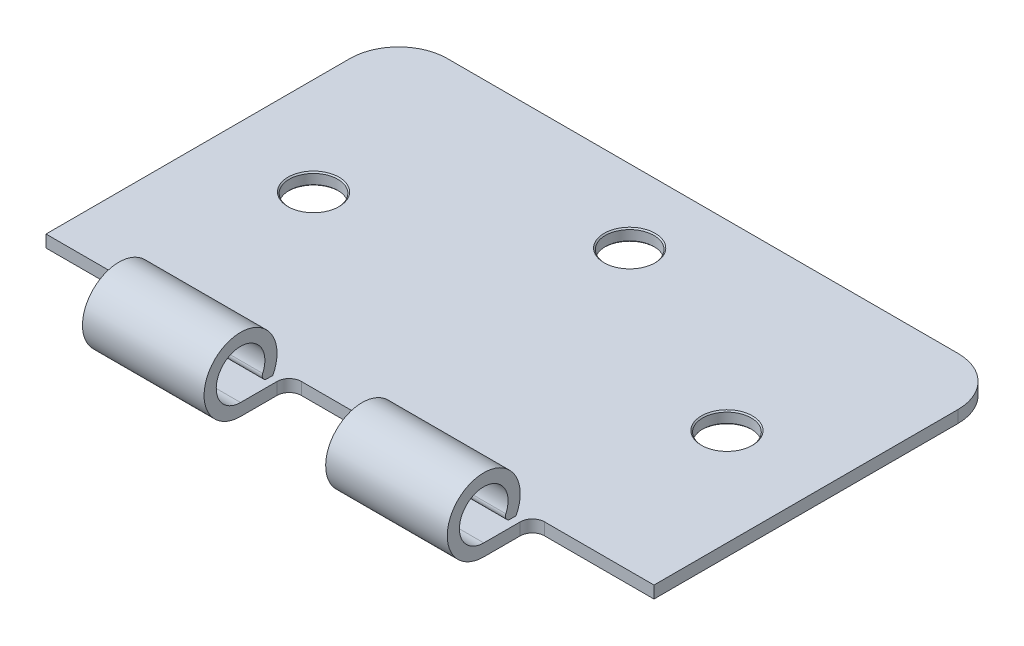
SolidWorks part; units mm, degrees
ref_plane "Front Plane" through (0, 0, 0) normal (0, 0, 1) x (1, 0, 0)
ref_plane "Top Plane" through (0, 0, 0) normal (0, 1, 0) x (1, 0, 0)
ref_plane "Right Plane" through (0, 0, 0) normal (1, 0, 0) x (0, 0, -1)
sketch "Sketch1" plane through (0, 0, 0) normal (0, 1, 0) x (1, 0, 0)
  line L1 (-105, 150) -> (105, 150)
  line L2 (-125, 130) -> (-125, 0)
  line L3 (-125, 0) -> (125, 0)
  line L4 (125, 130) -> (125, 0)
  line L5 (-125, 150) -> (125, 0) construction
  line L6 (-125, 0) -> (125, 150) construction
  arc A0 (105, 150) -> (125, 130) centre (105, 130) cw
  arc A1 (-105, 150) -> (-125, 130) centre (-105, 130) ccw
  circle A2 centre (-85, 75) radius 10
  circle A3 centre (85, 75) radius 10
  circle A4 centre (0, 120) radius 10
  point P0 (0, 75)
  dimension "D3" = 20
  dimension "D8" = 20
  dimension "D1" = 250
  dimension "D2" = 150
  dimension "D4" = 40
  dimension "D5" = 75
  dimension "D6" = 30
  dimension "D7" = 40
extrude "Boss-Extrude1" add sketch "Sketch1" along normal blind 5
sketch "Sketch2" plane through (0, 0, 0) normal (1, 0, 0) x (0, 0, -1)
  line L0 (0, 0) -> (130, 0) construction
  line L1 (0, 5) -> (0, 0) construction
  line L2 (0, 0) -> (-15, 0)
  line L3 (0, 5) -> (-15, 5)
  line L4 (-1.7335, 8) -> (-4.0913, 8)
  line L5 (0, 5) -> (130, 5) construction
  line L6 (0, 0) -> (0, 5)
  arc A0 (-1.7335, 8) -> (-15, 0) centre (-15, 15) ccw
  arc A1 (-5.9094, 10.8333) -> (-15, 5) centre (-15, 15) ccw
  arc A2 (-4.0913, 8) -> (-5.9094, 10.8333) centre (-4.0913, 10) cw
  dimension "D1" = 30
  dimension "D2" = 20
  dimension "D4" = 2
  dimension "D3" = 3
extrude "Boss-Extrude2" add sketch "Sketch2" along normal mid plane 250
sketch "Sketch3" plane through (0, 0, 0) normal (0, 1, 0) x (1, 0, 0)
  line L0 (-125, 0) -> (-125, -30) construction
  line L1 (-75, 5) -> (-125, 5)
  line L2 (-75, 5) -> (-75, -30)
  line L3 (-75, -30) -> (-125, -30)
  line L4 (-125, 5) -> (-125, -30)
  line L5 (-125, -30) -> (125, -30) construction
  line L7 (-25, -30) -> (25, -30)
  line L8 (-25, -30) -> (-25, 5)
  line L9 (-25, 5) -> (25, 5)
  line L10 (25, -30) -> (25, 5)
  line L11 (75, -30) -> (125, -30)
  line L12 (75, -30) -> (75, 5)
  line L13 (75, 5) -> (125, 5)
  line L14 (125, -30) -> (125, 5)
  dimension "D1" = 50
  dimension "D2" = 35
  dimension "D3" = 50
  dimension "D4" = 50
  dimension "D5" = 50
  dimension "D6" = 50
extrude "Cut-Extrude1" cut sketch "Sketch3" along normal mid plane 60
fillet "Fillet1" radius 5 4 edges at (-75, 2.5, -5) (-25, 2.5, -5) (25, 2.5, -5) (75, 2.5, -5)
chamfer "Chamfer1" distance 0.5 angle 45 6 edges at (85, 0, -65) (85, 5, -65) (0, 0, -110) (0, 5, -110) (-85, 0, -65) (-85, 5, -65)
